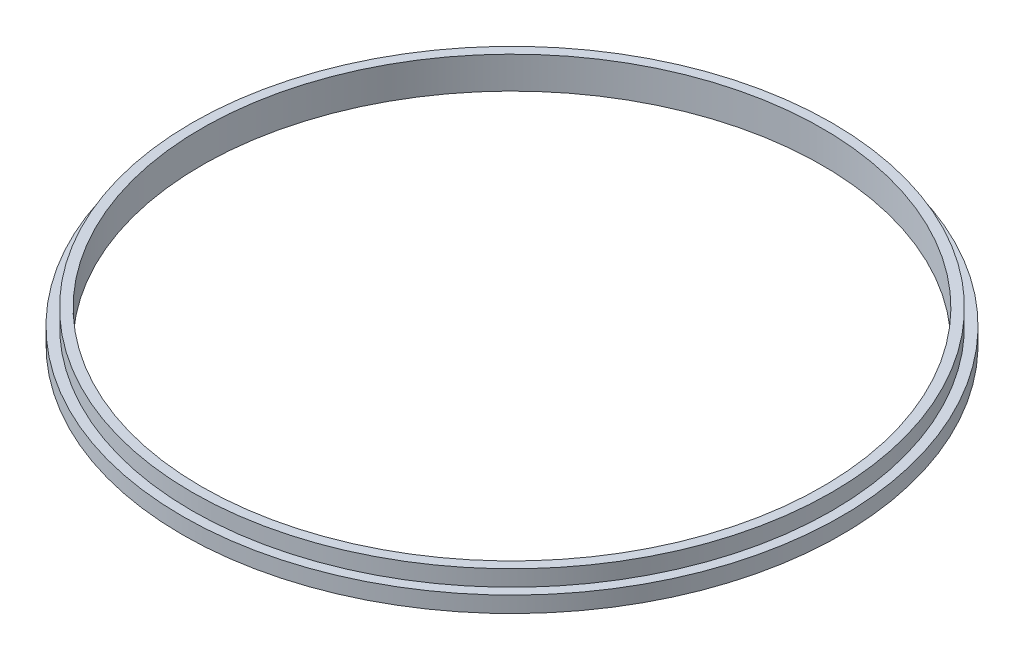
SolidWorks part; units mm, degrees
ref_plane "前视基准面" through (0, 0, 0) normal (0, 0, 1) x (1, 0, 0)
ref_plane "上视基准面" through (0, 0, 0) normal (0, 1, 0) x (1, 0, 0)
ref_plane "右视基准面" through (0, 0, 0) normal (1, 0, 0) x (0, 0, -1)
other "Configuration Table"
sketch "草图1" plane through (0, 0, 0) normal (0, 1, 0) x (1, 0, 0)
  circle A0 centre (0, 0) radius 103
  circle A1 centre (0, 0) radius 97
  dimension "D1" = 206
  dimension "D2" = 194
extrude "凸台-拉伸1" add sketch "草图1" along normal blind 5
sketch "草图2" plane through (0, 5, 0) normal (0, 1, 0) x (1, 0, 0)
  circle A0 centre (0, 0) radius 97
  circle A1 centre (0, 0) radius 100
  dimension "D1" = 194
  dimension "D2" = 200
extrude "凸台-拉伸2" add sketch "草图2" along normal blind 5
